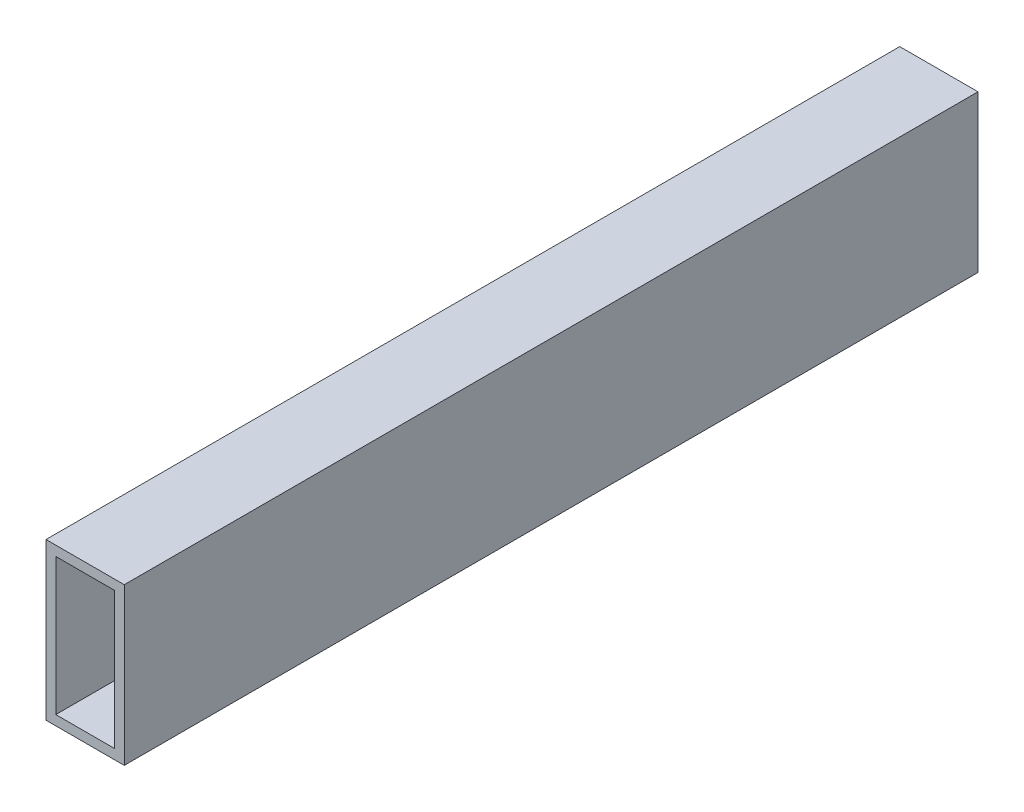
SolidWorks part; units mm, degrees
material "6061 Alloy"
ref_plane "Front Plane" through (0, 0, 0) normal (0, 0, 1) x (1, 0, 0)
ref_plane "Top Plane" through (0, 0, 0) normal (0, 1, 0) x (1, 0, 0)
ref_plane "Right Plane" through (0, 0, 0) normal (1, 0, 0) x (0, 0, -1)
sketch "Sketch1" plane through (0, 0, 0) normal (0, 0, 1) x (1, 0, 0)
  line L0 (0, 25.4) -> (0, 22.225) construction
  line L1 (-12.7, 25.4) -> (12.7, 25.4)
  line L2 (-12.7, 25.4) -> (-12.7, -25.4)
  line L3 (-12.7, -25.4) -> (12.7, -25.4)
  line L4 (12.7, 25.4) -> (12.7, -25.4)
  line L5 (-12.7, 25.4) -> (12.7, -25.4) construction
  line L6 (-12.7, -25.4) -> (12.7, 25.4) construction
  line L7 (-9.525, 22.225) -> (9.525, 22.225)
  line L8 (-9.525, 22.225) -> (-9.525, -22.225)
  line L9 (-9.525, -22.225) -> (9.525, -22.225)
  line L10 (9.525, 22.225) -> (9.525, -22.225)
  line L11 (9.525, 0) -> (12.7, 0) construction
  line L12 (-9.525, 0) -> (-12.7, 0) construction
  line L13 (0, -22.225) -> (0, -25.4) construction
  point P0 (0, 0)
  dimension "D1" = 50.8
  dimension "D2" = 25.4
  dimension "D3" = 3.175
extrude "Boss-Extrude1" add sketch "Sketch1" along normal blind 277.114
